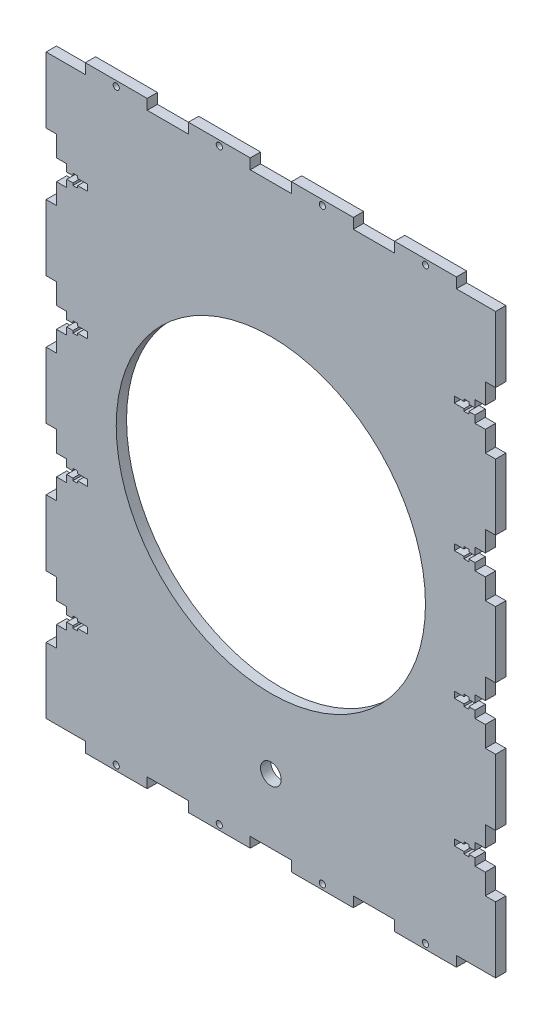
SolidWorks part; units mm, degrees
ref_plane "Front Plane" through (0, 0, 0) normal (0, 0, 1) x (1, 0, 0)
ref_plane "Top Plane" through (0, 0, 0) normal (0, 1, 0) x (1, 0, 0)
ref_plane "Right Plane" through (0, 0, 0) normal (1, 0, 0) x (0, 0, -1)
sketch "Sketch1" plane through (0, 0, 0) normal (0, 0, 1) x (1, 0, 0)
  line L0 (-90, 140) -> (-90, 145)
  line L1 (-90, 145) -> (-60, 145)
  line L2 (-60, 145) -> (-60, 140)
  line L3 (-60, 140) -> (-40, 140)
  line L4 (-40, 140) -> (-40, 145)
  line L5 (-40, 145) -> (-10, 145)
  line L6 (-10, 145) -> (-10, 140)
  line L7 (-10, 140) -> (10, 140)
  line L8 (10, 140) -> (10, 145)
  line L9 (10, 145) -> (40, 145)
  line L10 (40, 145) -> (40, 140)
  line L11 (40, 140) -> (60, 140)
  line L12 (60, 140) -> (60, 145)
  line L13 (90, 145) -> (90, 140)
  line L14 (90, 140) -> (109, 140)
  line L15 (-109, 140) -> (-90, 140)
  line L16 (-109, 140) -> (-90, 140) construction
  line L17 (-60, 140) -> (-40, 140) construction
  line L18 (-10, 140) -> (10, 140) construction
  line L19 (-60, 140) -> (-40, 140)
  line L20 (-40, 140) -> (-40, 145)
  line L21 (-93.701, 94.5) -> (-93.701, 95.6)
  line L22 (-10, 145) -> (-10, 140)
  line L23 (-10, 140) -> (10, 140)
  line L24 (10, 140) -> (10, 145)
  line L25 (10, 145) -> (40, 145)
  line L26 (40, 145) -> (40, 140)
  line L27 (40, 140) -> (60, 140)
  line L28 (60, 140) -> (60, 145)
  line L29 (60, 145) -> (90, 145)
  line L30 (90, 145) -> (90, 140)
  line L31 (90, 140) -> (109, 140)
  line L32 (-109, 140) -> (-109, 108)
  line L33 (-109, 108) -> (-104, 108)
  line L34 (-104, 108) -> (-104, 78)
  line L35 (-104, 78) -> (-109, 78)
  line L36 (-109, 78) -> (-109, 46)
  line L37 (-109, 46) -> (-104, 46)
  line L38 (-104, 46) -> (-104, 16)
  line L39 (-104, 16) -> (-109, 16)
  line L40 (-109, 16) -> (-109, -16)
  line L41 (-109, -16) -> (-104, -16)
  line L42 (-104, -16) -> (-104, -46)
  line L43 (-104, -46) -> (-109, -46)
  line L44 (-109, -46) -> (-109, -78)
  line L45 (-109, -78) -> (-104, -78)
  line L46 (-104, -78) -> (-104, -108)
  line L47 (-104, -108) -> (-109, -108)
  line L48 (-109, -108) -> (-109, -140)
  line L49 (-190.4328, 0) -> (140.4301, 0) construction
  line L50 (0, 200.958) -> (0, -156.4329) construction
  line L51 (109, 140) -> (109, 108)
  line L52 (109, -108) -> (109, -140)
  line L53 (104, -108) -> (109, -108)
  line L54 (104, -78) -> (104, -108)
  line L55 (109, -78) -> (104, -78)
  line L56 (109, -46) -> (109, -78)
  line L57 (104, -46) -> (109, -46)
  line L58 (104, -16) -> (104, -46)
  line L59 (109, -16) -> (104, -16)
  line L60 (109, 16) -> (109, -16)
  line L61 (104, 16) -> (109, 16)
  line L62 (104, 46) -> (104, 16)
  line L63 (109, 46) -> (104, 46)
  line L64 (109, 78) -> (109, 46)
  line L65 (104, 78) -> (109, 78)
  line L66 (104, 108) -> (104, 78)
  line L67 (109, 108) -> (104, 108)
  line L68 (-90, 140) -> (-109, 140)
  line L70 (-99.001, 94.5) -> (-99.001, 98)
  line L71 (-96.001, 94.5) -> (-99.001, 94.5)
  line L72 (-40, 140) -> (-60, 140)
  line L73 (-40, 145) -> (-40, 140)
  line L74 (-93.701, 90.4) -> (-93.701, 91.5)
  line L75 (-10, 140) -> (-10, 145)
  line L76 (10, 145) -> (10, 140)
  line L77 (40, 145) -> (10, 145)
  line L78 (40, 140) -> (40, 145)
  line L79 (60, 140) -> (40, 140)
  line L80 (60, 145) -> (90, 145)
  line L81 (60, 145) -> (60, 140)
  line L82 (90, 140) -> (90, 145)
  line L83 (109, 140) -> (90, 140)
  line L84 (-90, 140) -> (-109, 140)
  line L86 (-93.701, 95.6) -> (-96.001, 95.6)
  line L87 (-40, 140) -> (-60, 140)
  line L88 (-40, 145) -> (-40, 140)
  line L89 (-96.001, 91.5) -> (-96.001, 90.4)
  line L90 (-10, 140) -> (-10, 145)
  line L91 (10, 145) -> (10, 140)
  line L92 (40, 145) -> (10, 145)
  line L93 (40, 140) -> (40, 145)
  line L94 (60, 140) -> (40, 140)
  line L95 (60, 145) -> (60, 140)
  line L96 (90, 145) -> (60, 145)
  line L97 (90, 140) -> (90, 145)
  line L98 (90, -145) -> (90, -140)
  line L99 (60, -145) -> (90, -145)
  line L100 (90, -140) -> (109, -140)
  line L101 (60, -140) -> (60, -145)
  line L102 (40, -140) -> (60, -140)
  line L103 (40, -145) -> (40, -140)
  line L104 (10, -145) -> (40, -145)
  line L105 (-10, -140) -> (10, -140)
  line L106 (10, -140) -> (10, -145)
  line L107 (-10, -145) -> (-10, -140)
  line L108 (-40, -145) -> (-10, -145)
  line L109 (-40, -140) -> (-40, -145)
  line L110 (-60, -140) -> (-40, -140)
  line L111 (-60, -145) -> (-60, -140)
  line L112 (-90, -145) -> (-60, -145)
  line L113 (-90, -140) -> (-90, -145)
  line L114 (-109, -140) -> (-90, -140)
  line L115 (-89.001, 94.5) -> (-93.701, 94.5)
  line L116 (-89.001, 91.5) -> (-89.001, 94.5)
  line L117 (-93.701, 91.5) -> (-89.001, 91.5)
  line L118 (-96.001, 95.6) -> (-96.001, 94.5)
  line L119 (-96.001, 90.4) -> (-93.701, 90.4)
  line L120 (-99.001, 91.5) -> (-96.001, 91.5)
  line L121 (-99.001, 98) -> (-104.001, 98)
  line L122 (-104.001, 88) -> (-99.001, 88)
  line L123 (-99.001, 91.5) -> (-99.001, 88)
  line L124 (-93.701, 32.5) -> (-93.701, 33.6)
  line L125 (-99.001, 32.5) -> (-99.001, 36)
  line L126 (-96.001, 32.5) -> (-99.001, 32.5)
  line L127 (-93.701, 28.4) -> (-93.701, 29.5)
  line L128 (-93.701, 33.6) -> (-96.001, 33.6)
  line L129 (-96.001, 29.5) -> (-96.001, 28.4)
  line L130 (-89.001, 32.5) -> (-93.701, 32.5)
  line L131 (-89.001, 29.5) -> (-89.001, 32.5)
  line L132 (-93.701, 29.5) -> (-89.001, 29.5)
  line L133 (-96.001, 33.6) -> (-96.001, 32.5)
  line L134 (-96.001, 28.4) -> (-93.701, 28.4)
  line L135 (-99.001, 29.5) -> (-96.001, 29.5)
  line L136 (-99.001, 36) -> (-104.001, 36)
  line L137 (-104.001, 26) -> (-99.001, 26)
  line L138 (-99.001, 29.5) -> (-99.001, 26)
  line L139 (99.001, 29.5) -> (99.001, 26)
  line L140 (104.001, 26) -> (99.001, 26)
  line L141 (99.001, 36) -> (104.001, 36)
  line L142 (99.001, 29.5) -> (96.001, 29.5)
  line L143 (96.001, 28.4) -> (93.701, 28.4)
  line L144 (96.001, 33.6) -> (96.001, 32.5)
  line L145 (93.701, 29.5) -> (89.001, 29.5)
  line L146 (89.001, 29.5) -> (89.001, 32.5)
  line L147 (89.001, 32.5) -> (93.701, 32.5)
  line L148 (96.001, 29.5) -> (96.001, 28.4)
  line L149 (93.701, 33.6) -> (96.001, 33.6)
  line L150 (93.701, 28.4) -> (93.701, 29.5)
  line L151 (96.001, 32.5) -> (99.001, 32.5)
  line L152 (99.001, 32.5) -> (99.001, 36)
  line L153 (93.701, 32.5) -> (93.701, 33.6)
  line L154 (99.001, 91.5) -> (99.001, 88)
  line L155 (104.001, 88) -> (99.001, 88)
  line L156 (99.001, 98) -> (104.001, 98)
  line L157 (99.001, 91.5) -> (96.001, 91.5)
  line L158 (96.001, 90.4) -> (93.701, 90.4)
  line L159 (96.001, 95.6) -> (96.001, 94.5)
  line L160 (93.701, 91.5) -> (89.001, 91.5)
  line L161 (89.001, 91.5) -> (89.001, 94.5)
  line L162 (89.001, 94.5) -> (93.701, 94.5)
  line L163 (96.001, 91.5) -> (96.001, 90.4)
  line L164 (93.701, 95.6) -> (96.001, 95.6)
  line L165 (93.701, 90.4) -> (93.701, 91.5)
  line L166 (96.001, 94.5) -> (99.001, 94.5)
  line L167 (99.001, 94.5) -> (99.001, 98)
  line L168 (93.701, 94.5) -> (93.701, 95.6)
  line L169 (93.701, -94.5) -> (93.701, -95.6)
  line L170 (99.001, -94.5) -> (99.001, -98)
  line L171 (96.001, -94.5) -> (99.001, -94.5)
  line L172 (93.701, -90.4) -> (93.701, -91.5)
  line L173 (93.701, -95.6) -> (96.001, -95.6)
  line L174 (96.001, -91.5) -> (96.001, -90.4)
  line L175 (89.001, -94.5) -> (93.701, -94.5)
  line L176 (89.001, -91.5) -> (89.001, -94.5)
  line L177 (93.701, -91.5) -> (89.001, -91.5)
  line L178 (96.001, -95.6) -> (96.001, -94.5)
  line L179 (96.001, -90.4) -> (93.701, -90.4)
  line L180 (99.001, -91.5) -> (96.001, -91.5)
  line L181 (99.001, -98) -> (104.001, -98)
  line L182 (104.001, -88) -> (99.001, -88)
  line L183 (99.001, -91.5) -> (99.001, -88)
  line L184 (-99.001, -91.5) -> (-99.001, -88)
  line L185 (-104.001, -88) -> (-99.001, -88)
  line L186 (-99.001, -98) -> (-104.001, -98)
  line L187 (-99.001, -91.5) -> (-96.001, -91.5)
  line L188 (-96.001, -90.4) -> (-93.701, -90.4)
  line L189 (-96.001, -95.6) -> (-96.001, -94.5)
  line L190 (-93.701, -91.5) -> (-89.001, -91.5)
  line L191 (-89.001, -91.5) -> (-89.001, -94.5)
  line L192 (-89.001, -94.5) -> (-93.701, -94.5)
  line L193 (-96.001, -91.5) -> (-96.001, -90.4)
  line L194 (-93.701, -95.6) -> (-96.001, -95.6)
  line L195 (-93.701, -90.4) -> (-93.701, -91.5)
  line L196 (-96.001, -94.5) -> (-99.001, -94.5)
  line L197 (-99.001, -94.5) -> (-99.001, -98)
  line L198 (-93.701, -94.5) -> (-93.701, -95.6)
  line L199 (93.701, -32.5) -> (93.701, -33.6)
  line L200 (99.001, -32.5) -> (99.001, -36)
  line L201 (96.001, -32.5) -> (99.001, -32.5)
  line L202 (93.701, -28.4) -> (93.701, -29.5)
  line L203 (93.701, -33.6) -> (96.001, -33.6)
  line L204 (96.001, -29.5) -> (96.001, -28.4)
  line L205 (89.001, -32.5) -> (93.701, -32.5)
  line L206 (89.001, -29.5) -> (89.001, -32.5)
  line L207 (93.701, -29.5) -> (89.001, -29.5)
  line L208 (96.001, -33.6) -> (96.001, -32.5)
  line L209 (96.001, -28.4) -> (93.701, -28.4)
  line L210 (99.001, -29.5) -> (96.001, -29.5)
  line L211 (99.001, -36) -> (104.001, -36)
  line L212 (104.001, -26) -> (99.001, -26)
  line L213 (99.001, -29.5) -> (99.001, -26)
  line L214 (-99.001, -29.5) -> (-99.001, -26)
  line L215 (-104.001, -26) -> (-99.001, -26)
  line L216 (-99.001, -36) -> (-104.001, -36)
  line L217 (-99.001, -29.5) -> (-96.001, -29.5)
  line L218 (-96.001, -28.4) -> (-93.701, -28.4)
  line L219 (-96.001, -33.6) -> (-96.001, -32.5)
  line L220 (-93.701, -29.5) -> (-89.001, -29.5)
  line L221 (-89.001, -29.5) -> (-89.001, -32.5)
  line L222 (-89.001, -32.5) -> (-93.701, -32.5)
  line L223 (-96.001, -29.5) -> (-96.001, -28.4)
  line L224 (-93.701, -33.6) -> (-96.001, -33.6)
  line L225 (-93.701, -28.4) -> (-93.701, -29.5)
  line L226 (-96.001, -32.5) -> (-99.001, -32.5)
  line L227 (-99.001, -32.5) -> (-99.001, -36)
  line L228 (-93.701, -32.5) -> (-93.701, -33.6)
  circle A0 centre (0, 0) radius 75
  circle A1 centre (0, -108.7399) radius 5
  circle A2 centre (-75, 142.5) radius 1.5
  circle A3 centre (-25, 142.5) radius 1.5
  circle A4 centre (25, 142.5) radius 1.5
  circle A5 centre (75, 142.5) radius 1.5
  circle A6 centre (75, -142.5) radius 1.5
  circle A7 centre (25, -142.5) radius 1.5
  circle A8 centre (-25, -142.5) radius 1.5
  circle A9 centre (-75, -142.5) radius 1.5
  point P39 (0, 0)
  dimension "D4" = 150
  dimension "D5" = 10
  dimension "D3" = 2.5
  dimension "D7" = 2.5
  dimension "D1" = 5
  dimension "D2" = 30
  dimension "D6" = 15
  dimension "D8" = 15
  dimension "D9" = 10
  dimension "D10" = 10
  dimension "D11" = 290
extrude "Boss-Extrude1" add sketch "Sketch1" along normal blind 5
